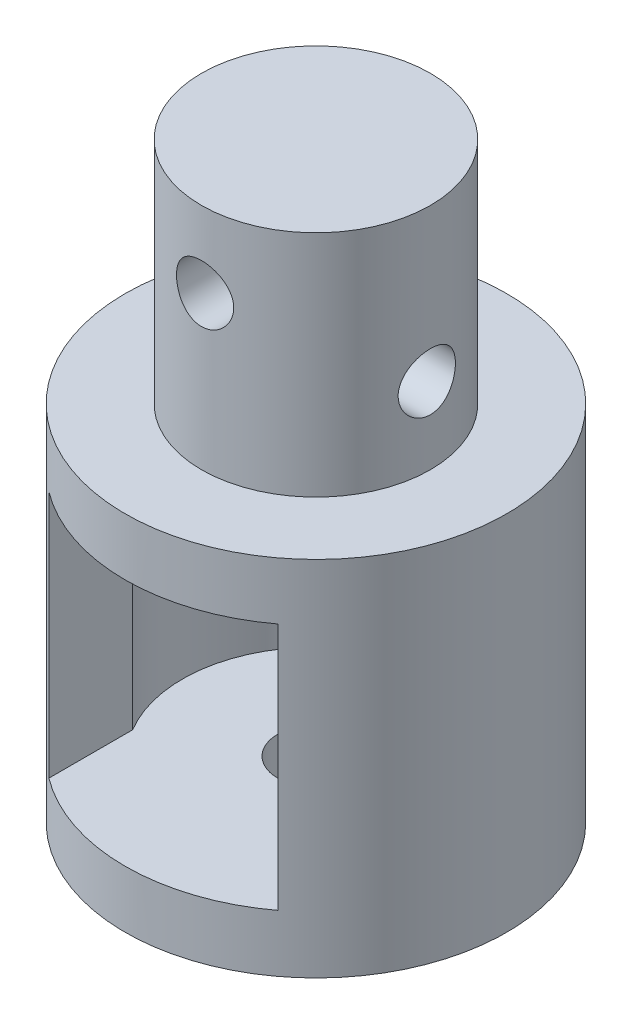
SolidWorks part; units mm, degrees
ref_plane "前视基准面" through (0, 0, 0) normal (0, 0, 1) x (1, 0, 0)
ref_plane "上视基准面" through (0, 0, 0) normal (0, 1, 0) x (1, 0, 0)
ref_plane "右视基准面" through (0, 0, 0) normal (1, 0, 0) x (0, 0, -1)
sketch "草图1" plane through (0, 0, 0) normal (0, 0, 1) x (1, 0, 0)
  line L0 (0, 0) -> (10, 0)
  line L1 (10, 0) -> (10, 19)
  line L2 (10, 19) -> (6, 19)
  line L3 (6, 19) -> (6, 31)
  line L4 (6, 31) -> (0, 31)
  line L5 (0, 31) -> (0, 0)
  dimension "D1" = 10
  dimension "D2" = 19
  dimension "D3" = 4
  dimension "D4" = 12
revolve "旋转1" add sketch "草图1" angle 360 about L5
ref_plane "基准面1" through (0, 3, 0) normal (0, 1, 0) x (1, 0, 0)
sketch "草图2" plane through (0, 3, 0) normal (0, 1, 0) x (1, 0, 0)
  circle A0 centre (0, 0) radius 7
extrude "切除-拉伸1" cut sketch "草图2" along normal blind 13
sketch "草图3" plane through (0, 0, 0) normal (0, 0, 1) x (1, 0, 0)
  line L0 (0, 3) -> (6, 3)
  line L1 (11, 3) -> (-11, 3) construction
  line L2 (6, 3) -> (6, 16)
  line L3 (6, 16) -> (-6, 16)
  line L4 (-6, 16) -> (-6, 3)
  line L5 (-6, 3) -> (0, 3)
  line L6 (0, 3) -> (0, 23) construction
extrude "切除-拉伸2" cut sketch "草图3" along normal blind 18
sketch "草图4" plane through (0, 0, 0) normal (0, 0, 1) x (1, 0, 0)
  line L0 (0, 0) -> (0, 27) construction
  circle A0 centre (0, 27) radius 1.5
extrude "切除-拉伸3" cut sketch "草图4" against normal through all both and the other way through all
sketch "草图5" plane through (0, 0, 0) normal (0, -1, 0) x (1, 0, 0)
  circle A0 centre (0, 0) radius 2
extrude "切除-拉伸4" cut sketch "草图5" against normal blind 4
sketch "草图6" plane through (0, 0, 0) normal (1, 0, 0) x (0, 0, -1)
  line L0 (0, 31) -> (0, 23) construction
  line L1 (6, 31) -> (-6, 31) construction
  circle A0 centre (0, 23) radius 1.5
extrude "切除-拉伸5" cut sketch "草图6" against normal through all both and the other way through all
